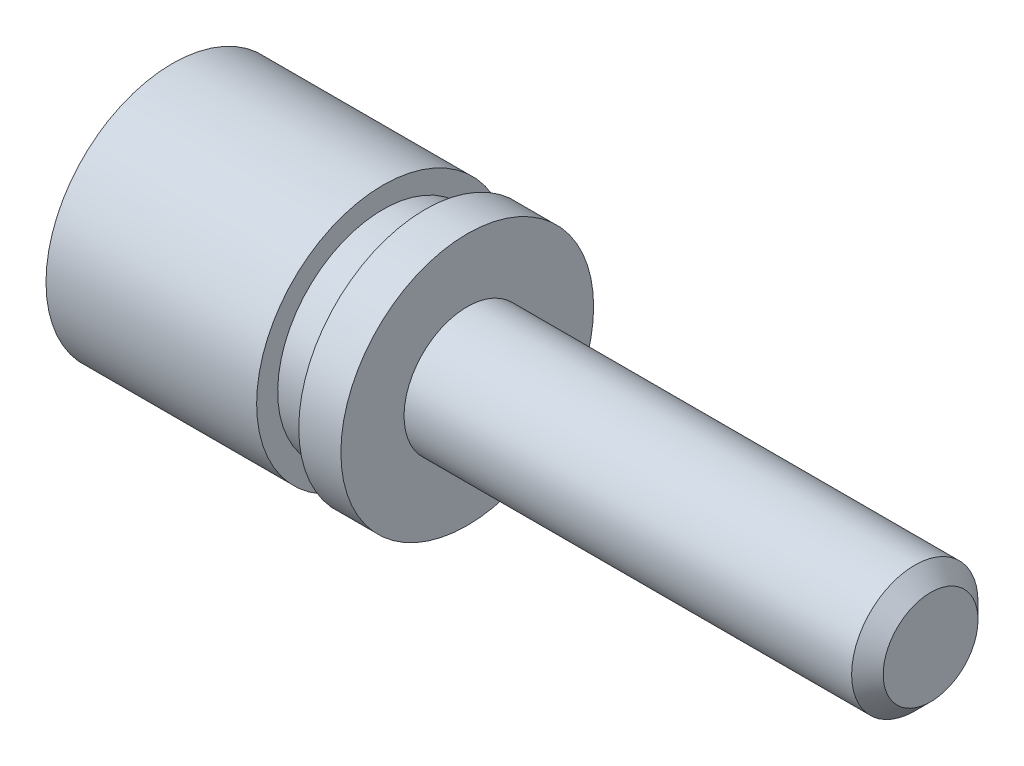
SolidWorks part; units mm, degrees
ref_plane "Plan1" through (0, 0, 0) normal (0, 0, 1) x (1, 0, 0)
ref_plane "Plan2" through (0, 0, 0) normal (0, 1, 0) x (1, 0, 0)
ref_plane "Plan3" through (0, 0, 0) normal (1, 0, 0) x (0, 0, -1)
sketch "Esquisse1" plane through (0, 0, 0) normal (0, 0, 1) x (1, 0, 0)
  line L0 (0, 6) -> (10, 6)
  line L1 (-3, 0) -> (36, 0) construction
  line L2 (10, 6) -> (10, 5)
  line L3 (12, 6) -> (12, 5)
  line L4 (10, 5) -> (12, 5)
  line L5 (14, 6) -> (14, 3)
  line L6 (14, 3) -> (36, 3)
  line L7 (12, 6) -> (14, 6)
  line L8 (36, 3) -> (36, 0)
  line L9 (36, 0) -> (-1.6619, 0)
  arc A0 (0, 6) -> (-1.6619, 0) centre (10, 0) ccw
  dimension "D2" = 22
  dimension "D1" = 6
  dimension "D3" = 14
revolve "Base-Révolution" add sketch "Esquisse1" angle 360 about L1
chamfer "Chanfrein1" distance 0.75 angle 45
sketch "Esquisse2" plane through (0, 0, 0) normal (0, 0, 1) x (1, 0, 0)
  line L0 (35.25, 0) -> (36, 0) construction
  point P1 (10, 0)
  dimension "D1" = 10
